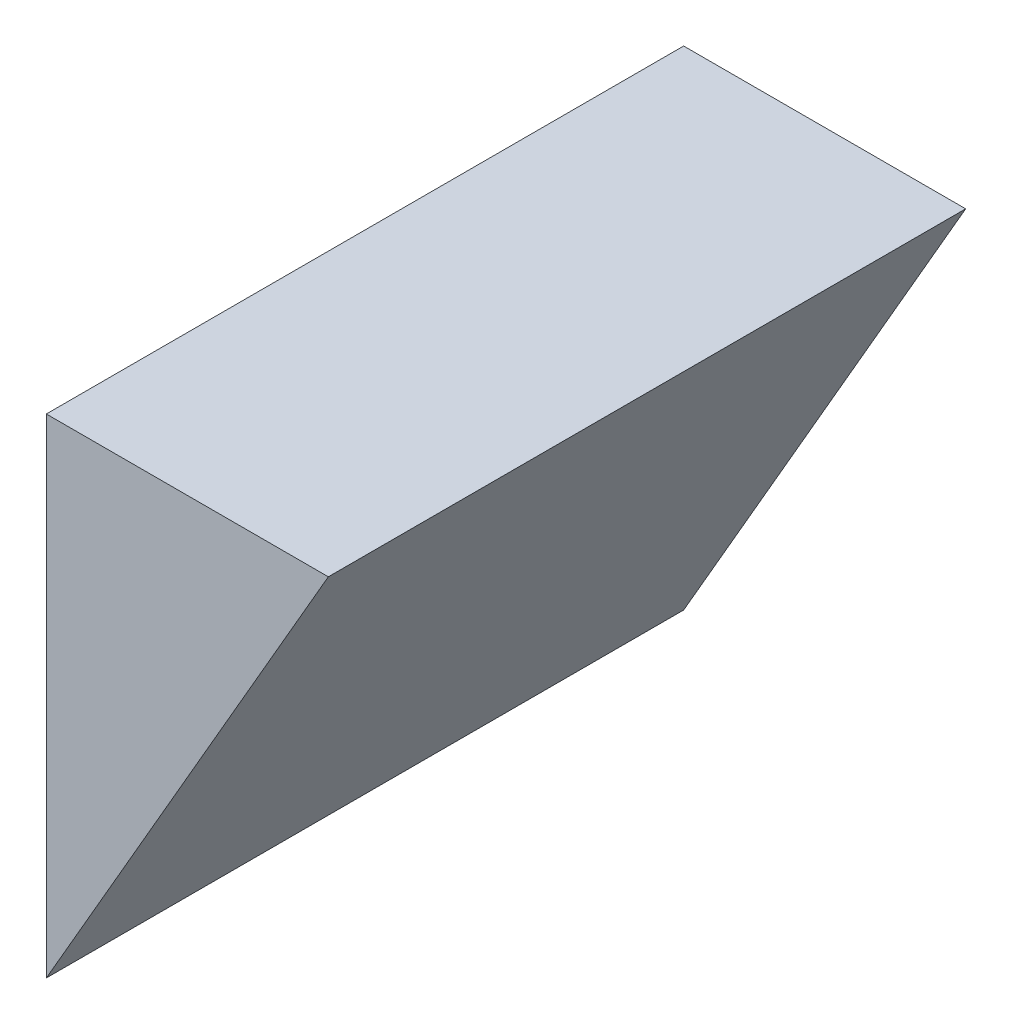
SolidWorks part; units mm, degrees
ref_plane "Front Plane" through (0, 0, 0) normal (0, 0, 1) x (1, 0, 0)
ref_plane "Top Plane" through (0, 0, 0) normal (0, 1, 0) x (1, 0, 0)
ref_plane "Right Plane" through (0, 0, 0) normal (1, 0, 0) x (0, 0, -1)
sketch "Sketch1" plane through (0, 0, 0) normal (0, 0, 1) x (1, 0, 0)
  line L0 (0, 0) -> (0, -30.1204)
  line L1 (0, -30.1204) -> (17.39, 0)
  line L2 (17.39, 0) -> (0, 0)
  dimension "D1" = 30
  dimension "D2" = 17.39
extrude "Boss-Extrude2" add sketch "Sketch1" along normal blind 39.3
